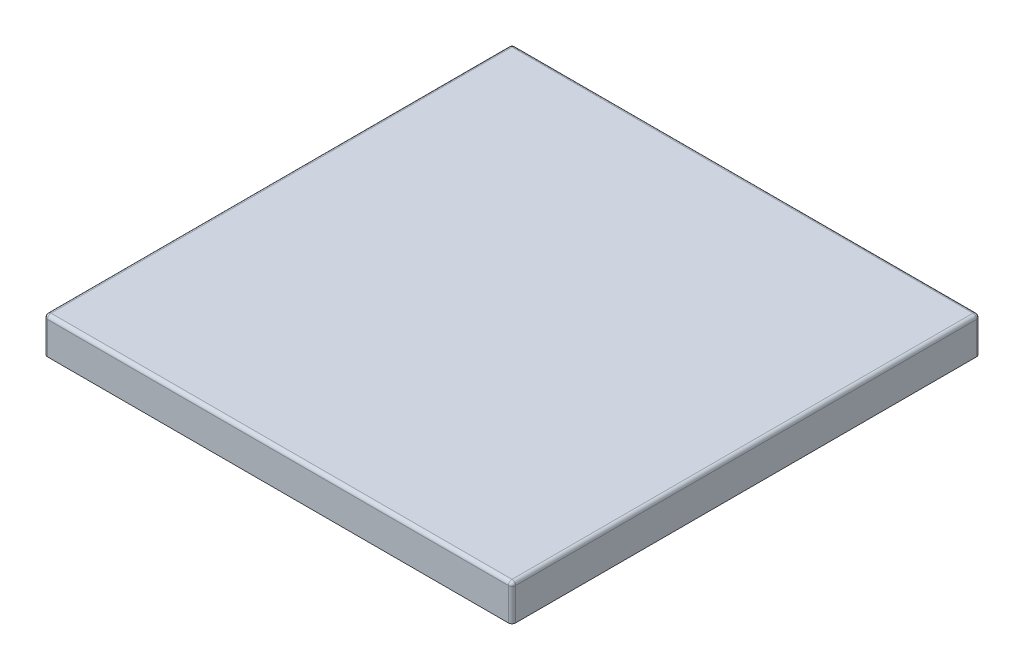
SolidWorks part; units mm, degrees
ref_plane "Front Plane" through (0, 0, 0) normal (0, 0, 1) x (1, 0, 0)
ref_plane "Top Plane" through (0, 0, 0) normal (0, 1, 0) x (1, 0, 0)
ref_plane "Right Plane" through (0, 0, 0) normal (1, 0, 0) x (0, 0, -1)
sketch "Sketch1" plane through (0, 0, 0) normal (0, 1, 0) x (1, 0, 0)
  line L1 (-65, -65) -> (65, -65)
  line L2 (-65, -65) -> (-65, 65)
  line L3 (-65, 65) -> (65, 65)
  line L4 (65, -65) -> (65, 65)
  line L5 (-65, -65) -> (65, 65) construction
  line L6 (-65, 65) -> (65, -65) construction
  point P0 (0, 0)
  dimension "D1" = 130
extrude "Boss-Extrude1" add sketch "Sketch1" along normal blind 10
fillet "Fillet1" radius 1 4 edges at (-65, 5, 65) (65, 5, 65) (65, 5, -65) (-65, 5, -65)
fillet "Fillet2" radius 1 8 edges at (-64.7071, 10, -64.7071) (0, 10, -65) (64.7071, 10, -64.7071) (65, 10, 0) (64.7071, 10, 64.7071) (0, 10, 65) (-64.7071, 10, 64.7071) (-65, 10, 0)
